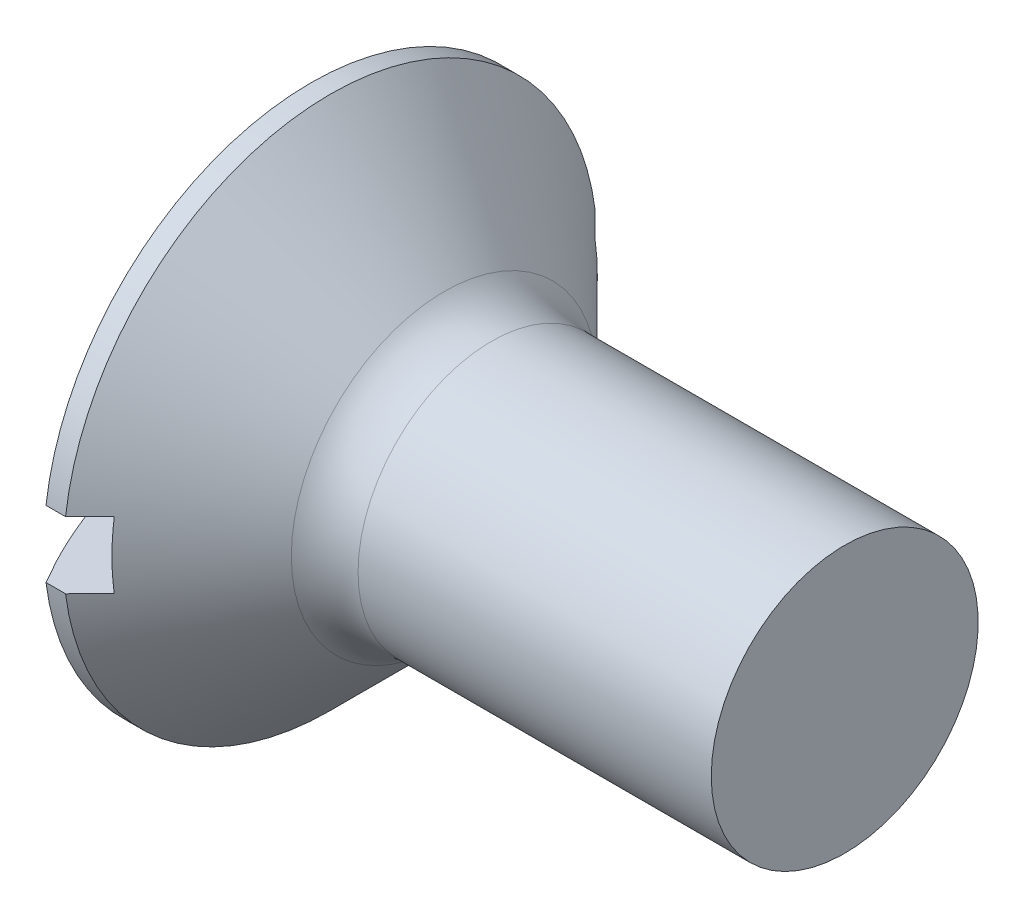
SolidWorks part; units mm, degrees
ref_plane "Front" through (0, 0, 0) normal (0, 0, 1) x (1, 0, 0)
ref_plane "Top" through (0, 0, 0) normal (0, 1, 0) x (1, 0, 0)
ref_plane "Right" through (0, 0, 0) normal (1, 0, 0) x (0, 0, -1)
sketch "Ske-Screw" plane through (0, 0, 0) normal (0, 0, 1) x (1, 0, 0)
  line L0 (2.7593, 10) -> (3.4916, 10)
  line L1 (2.7593, 0) -> (0, 0)
  line L2 (9.5271, 5) -> (22.7593, 5)
  line L3 (22.7593, 5) -> (22.7593, 0)
  line L4 (22.7593, 0) -> (2.7593, 0)
  line L5 (-1.3499, 0) -> (8.9842, 0) construction
  line L6 (3.4916, 10) -> (7.7593, 5.7322)
  arc A0 (2.7593, 10) -> (0, 0) centre (19.5, 0) ccw
  arc A1 (7.7593, 5.7322) -> (9.5271, 5) centre (9.5271, 7.5) ccw
  dimension "rf" = 19.5
  dimension "r" = 2.5
  dimension "l" = 20
  dimension "dk" = 20
  dimension "d" = 10
  dimension "k" = 5
  dimension "D3" = 45
revolve "Base" add sketch "Ske-Screw" angle 360 about L5
cosmetic thread "ThreadCosmetic1" parameters "D1"=15, "D2"=8.376
sketch "Ske-Slot" plane through (0, 0, 0) normal (0, 0, 1) x (1, 0, 0)
  line L1 (-1.3728, 0) -> (2.5237, 0) construction
  line L2 (0, -1.25) -> (4.4, -1.25)
  line L3 (0, -1.25) -> (0, 1.25)
  line L4 (0, 1.25) -> (4.4, 1.25)
  line L5 (4.4, -1.25) -> (4.4, 1.25)
  arc A0 (2.7593, 10) -> (2.7593, -10) centre (19.5, 0) ccw construction
  dimension "n" = 2.5
  dimension "t" = 4.4
extrude "Slot" cut sketch "Ske-Slot" against normal through all and the other way through all
sketch "Sketch1" plane through (0, 0, 0) normal (0, 0, 1) x (1, 0, 0)
  line L0 (5.8578, 0) -> (-1.624, 0) construction
  line L1 (7.7593, 9.188) -> (-15.2407, 9.188)
  line L2 (7.7593, 9.188) -> (7.7593, 4.188)
  line L3 (7.7593, 4.188) -> (-19.0407, 4.188)
  line L4 (-15.2407, 9.188) -> (-15.2407, 5)
  line L6 (2.7593, 10) -> (2.7593, 1.25) construction
  line L7 (22.7593, -5) -> (22.7593, 5) construction
  line L9 (9.5271, 5) -> (22.7593, 5) construction
  line L10 (-15.2407, 5) -> (-19.0407, 4.188)
  dimension "b" = 38
  dimension "D4" = 5
  dimension "x" = 3.8
  dimension "k" = 5
  dimension "D2" = 8.376
sketch "Sketch2" plane through (0, 0, 0) normal (0, 0, 1) x (1, 0, 0)
  line L0 (22.7593, 4.2968) -> (23.1653, 5)
  line L1 (23.1653, 5) -> (23.1653, 5.812)
  line L2 (23.1653, 5.812) -> (22.3533, 5.812)
  line L3 (22.3533, 5.812) -> (22.3533, 5)
  line L4 (22.3533, 5) -> (22.7593, 4.2968)
  line L5 (0, 0) -> (7.193, 0) construction
  line L6 (22.7593, -5) -> (22.7593, 5) construction
  dimension "D1" = 10
  dimension "D2" = 0.812
revolve "Cut-Revolve10" [suppressed] cut sketch "Sketch2" angle 360 about L5
pattern_linear "LPattern10" [suppressed] count 14 spacing 0.9744 along (1, 0, 0)
equation "\"D1@Sketch2\" = \"d@Ske-Screw\""
equation "\"D2@Sketch2\" =  ( \"d@Ske-Screw\" - \"D2@ThreadCosmetic1\" )  / 2"
equation "\"D3@LPattern10\" = \"D2@Sketch2\" * 1.2"
equation "\"D1@LPattern10\" = \"D1@ThreadCosmetic1\" / \"D3@LPattern10\" - 1"
